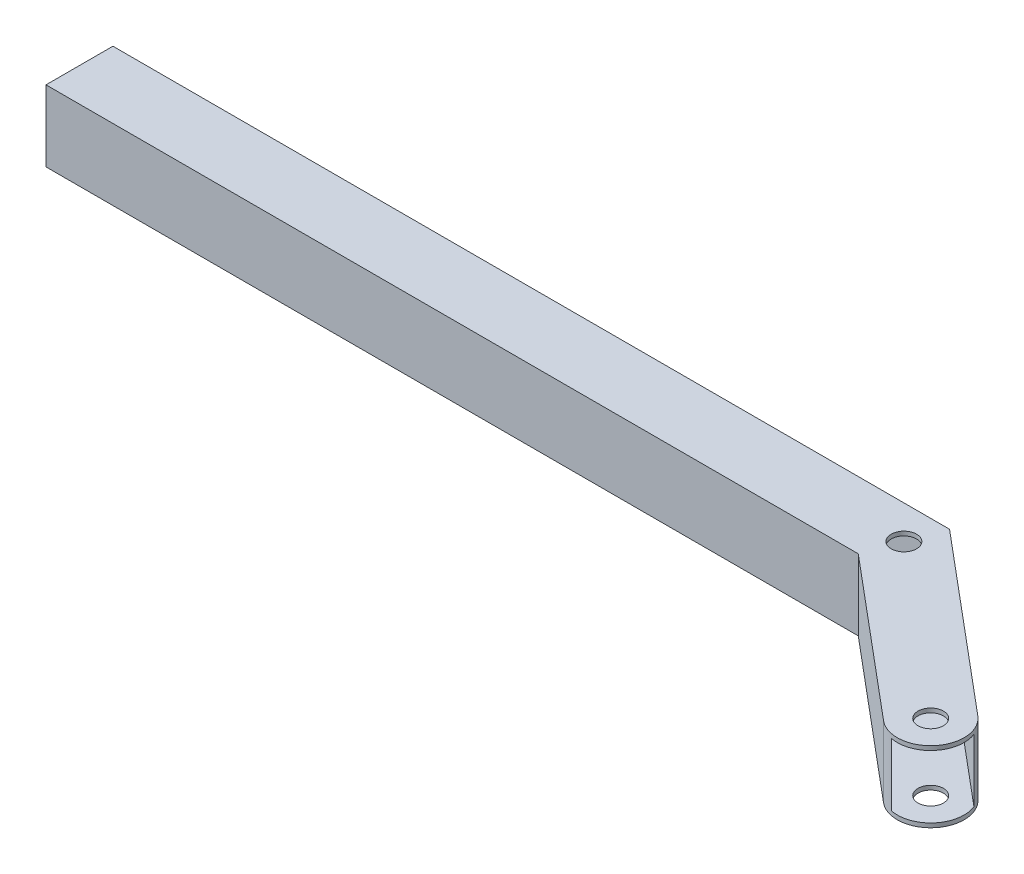
SolidWorks part; units mm, degrees
ref_plane "Front Plane" through (0, 0, 0) normal (0, 0, 1) x (1, 0, 0)
ref_plane "Top Plane" through (0, 0, 0) normal (0, 1, 0) x (1, 0, 0)
ref_plane "Right Plane" through (0, 0, 0) normal (1, 0, 0) x (0, 0, -1)
sketch "Sketch1" plane through (0, 0, 0) normal (0, 1, 0) x (1, 0, 0)
  line L0 (167.5905, -102.4842) -> (107.8945, -52.3933)
  line L1 (107.8945, -52.3933) -> (-200.4111, -52.3933)
  line L2 (-200.4111, -52.3933) -> (-200.4111, -26.9933)
  line L3 (-200.4111, -26.9933) -> (117.1394, -26.9933)
  line L4 (117.1394, -26.9933) -> (183.9173, -83.0266)
  arc A0 (183.9173, -83.0266) -> (167.5905, -102.4842) centre (175.7539, -92.7554) cw
extrude "Boss-Extrude1" add sketch "Sketch1" along normal blind 1.5875
sketch "Sketch2" plane through (0, 1.5875, 0) normal (0, 1, 0) x (1, 0, 0)
  line L0 (187.6068, -88.1948) -> (117.1394, -29.0656)
  line L1 (117.1394, -29.0656) -> (117.1394, -28.5808)
  line L2 (117.1394, -28.5808) -> (116.5615, -28.5808)
  line L3 (116.5615, -28.5808) -> (116.1189, -28.2094)
  line L4 (116.1189, -28.2094) -> (115.8073, -28.5808)
  line L5 (115.8073, -28.5808) -> (-200.4111, -28.5808)
  line L6 (-200.4111, -28.5808) -> (-200.4111, -26.9933)
  line L7 (-200.4111, -26.9933) -> (117.1394, -26.9933)
  line L8 (117.1394, -26.9933) -> (183.9173, -83.0266)
  line L9 (-200.4111, -52.3933) -> (-200.4111, -50.8058)
  line L10 (-200.4111, -50.8058) -> (108.4723, -50.8058)
  line L11 (108.4723, -50.8058) -> (173.3208, -105.2202)
  line L12 (167.5905, -102.4842) -> (107.8945, -52.3933)
  line L13 (107.8945, -52.3933) -> (-200.4111, -52.3933)
  arc A0 (183.9173, -83.0266) -> (187.6068, -88.1948) centre (175.7539, -92.7554) cw
  arc A1 (173.3208, -105.2202) -> (167.5905, -102.4842) centre (175.7539, -92.7554) cw
extrude "Boss-Extrude2" add sketch "Sketch2" along normal blind 25.4
sketch "Sketch6" plane through (0, 26.9875, 0) normal (0, 1, 0) x (1, 0, 0)
  line L0 (-200.4111, -26.9933) -> (117.1394, -26.9933)
  line L5 (107.8945, -52.3933) -> (-200.4111, -52.3933)
  line L6 (167.5905, -102.4842) -> (107.8945, -52.3933)
  line L7 (117.1394, -26.9933) -> (183.9173, -83.0266)
  line L8 (-200.4111, -26.9933) -> (-200.4111, -52.3933)
  arc A1 (183.9173, -83.0266) -> (167.5905, -102.4842) centre (175.7539, -92.7554) cw
extrude "Boss-Extrude3" add sketch "Sketch6" against normal blind 1.5875
sketch "Sketch7" plane through (0, 26.9875, 0) normal (0, 1, 0) x (1, 0, 0)
  circle A0 centre (175.7539, -92.7554) radius 4.826
  circle A1 centre (112.5169, -39.6933) radius 4.826
extrude "Cut-Extrude1" cut sketch "Sketch7" against normal blind 45.2755
